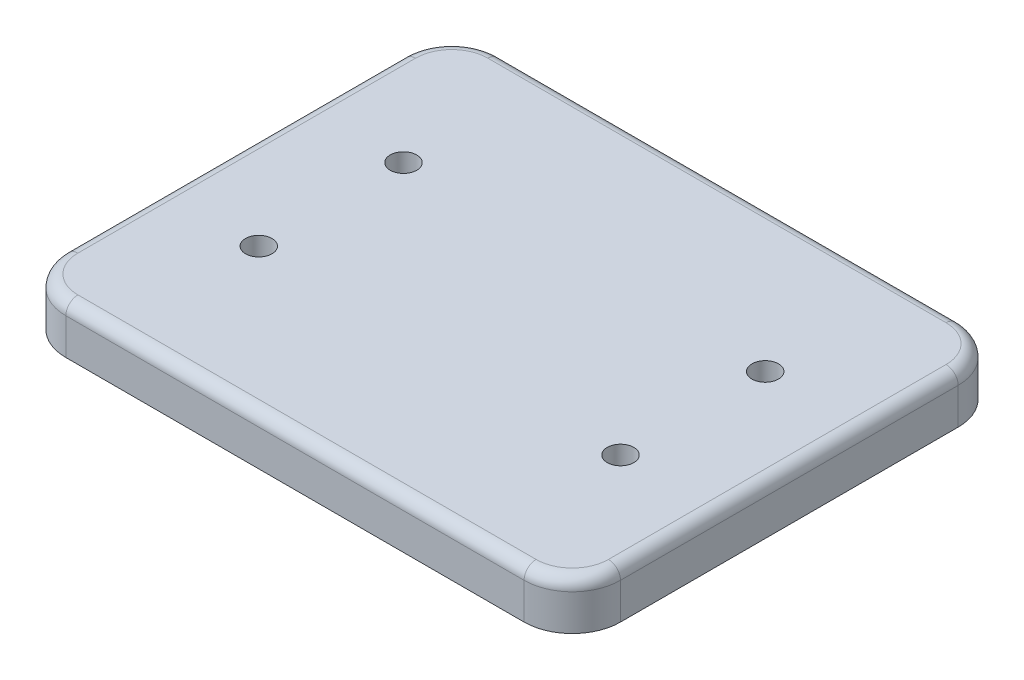
SolidWorks part; units mm, degrees
ref_plane "Front Plane" through (0, 0, 0) normal (0, 0, 1) x (1, 0, 0)
ref_plane "Top Plane" through (0, 0, 0) normal (0, 1, 0) x (1, 0, 0)
ref_plane "Right Plane" through (0, 0, 0) normal (1, 0, 0) x (0, 0, -1)
sketch "Sketch1" plane through (0, 0, 0) normal (0, 1, 0) x (1, 0, 0)
  line L0 (0, 90) -> (0, 0) construction
  line L1 (95, -90) -> (-95, -90)
  line L2 (115, -70) -> (115, 70)
  line L3 (95, 90) -> (-95, 90)
  line L4 (-115, -70) -> (-115, 70)
  line L5 (0, 0) -> (115, 0) construction
  line L7 (75, -30) -> (-75, -30) construction
  line L8 (75, -30) -> (75, 30) construction
  line L9 (75, 30) -> (-75, 30) construction
  line L10 (-75, -30) -> (-75, 30) construction
  line L12 (75, 30) -> (-75, -30) construction
  circle A0 centre (-75, 30) radius 5.5
  circle A1 centre (75, 30) radius 5.5
  circle A2 centre (75, -30) radius 5.5
  circle A3 centre (-75, -30) radius 5.5
  arc A4 (95, -90) -> (115, -70) centre (95, -70) ccw
  arc A5 (115, 70) -> (95, 90) centre (95, 70) ccw
  arc A6 (-95, 90) -> (-115, 70) centre (-95, 70) ccw
  arc A7 (-95, -90) -> (-115, -70) centre (-95, -70) cw
  point P0 (0, 0)
  point P1 (0, 0)
  point P6 (0, 0)
  dimension "D3" = 20
  dimension "D6" = 11
  dimension "D1" = 150
  dimension "D2" = 230
  dimension "D4" = 60
  dimension "D5" = 180
extrude "Boss-Extrude1" add sketch "Sketch1" along normal blind 20
sketch "Sketch2" plane through (0, 0, 0) normal (0, -1, 0) x (1, 0, 0)
  circle A22 centre (-75, 30) radius 9
  circle A23 centre (-75, 30) radius 9
  circle A32 centre (75, 30) radius 9
  circle A33 centre (75, 30) radius 9
  circle A35 centre (75, -30) radius 9
  circle A36 centre (75, -30) radius 9
  circle A38 centre (-75, -30) radius 9
  circle A39 centre (-75, -30) radius 9
  dimension "D2" = 3.5
  dimension "D1" = 3.5
  dimension "D3" = 3.5
  dimension "D4" = 3.5
extrude "Cut-Extrude1" cut sketch "Sketch2" against normal blind 11
fillet "Fillet1" radius 5 8 edges at (-109.1421, 20, 84.1421) (-115, 20, 0) (-109.1421, 20, -84.1421) (0, 20, -90) (109.1421, 20, -84.1421) (115, 20, 0) (109.1421, 20, 84.1421) (0, 20, 90)
